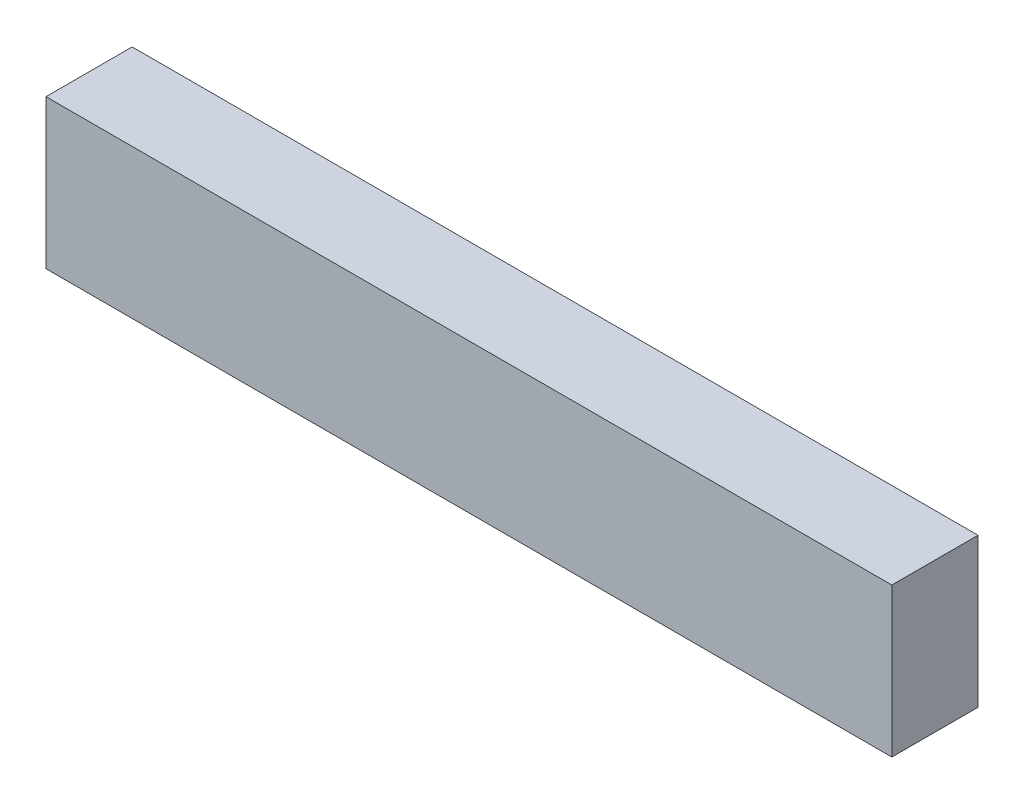
SolidWorks part; units mm, degrees
ref_plane "Front Plane" through (0, 0, 0) normal (0, 0, 1) x (1, 0, 0)
ref_plane "Top Plane" through (0, 0, 0) normal (0, 1, 0) x (1, 0, 0)
ref_plane "Right Plane" through (0, 0, 0) normal (1, 0, 0) x (0, 0, -1)
sketch "Sketch1" plane through (0, 0, 0) normal (0, 0, 1) x (1, 0, 0)
  line L0 (7.6645, 62.27) -> (79.2368, 62.27) construction
  line L1 (7.8645, 62.07) -> (79.0368, 62.07)
  line L2 (7.8645, 62.07) -> (7.8645, 49.53)
  line L3 (7.8645, 49.53) -> (79.0368, 49.53)
  line L4 (79.0368, 62.07) -> (79.0368, 49.53)
  line L5 (79.2368, 49.33) -> (79.2368, 62.27) construction
  line L6 (79.2368, 49.33) -> (7.6645, 49.33) construction
  line L7 (7.6645, 49.33) -> (7.6645, 62.27) construction
  dimension "D1" = 0.2
  dimension "D2" = 0.2
  dimension "D3" = 0.2
  dimension "D4" = 0.2
extrude "Boss-Extrude1" add sketch "Sketch1" along normal blind 7.25 contours L1 L4 L3 L2
shell "Shell1" thickness 0.5
equation "\"D2@Sketch1\"=\"D1@Sketch1\""
equation "\"D3@Sketch1\"=\"D1@Sketch1\""
equation "\"D4@Sketch1\"=\"D1@Sketch1\""
